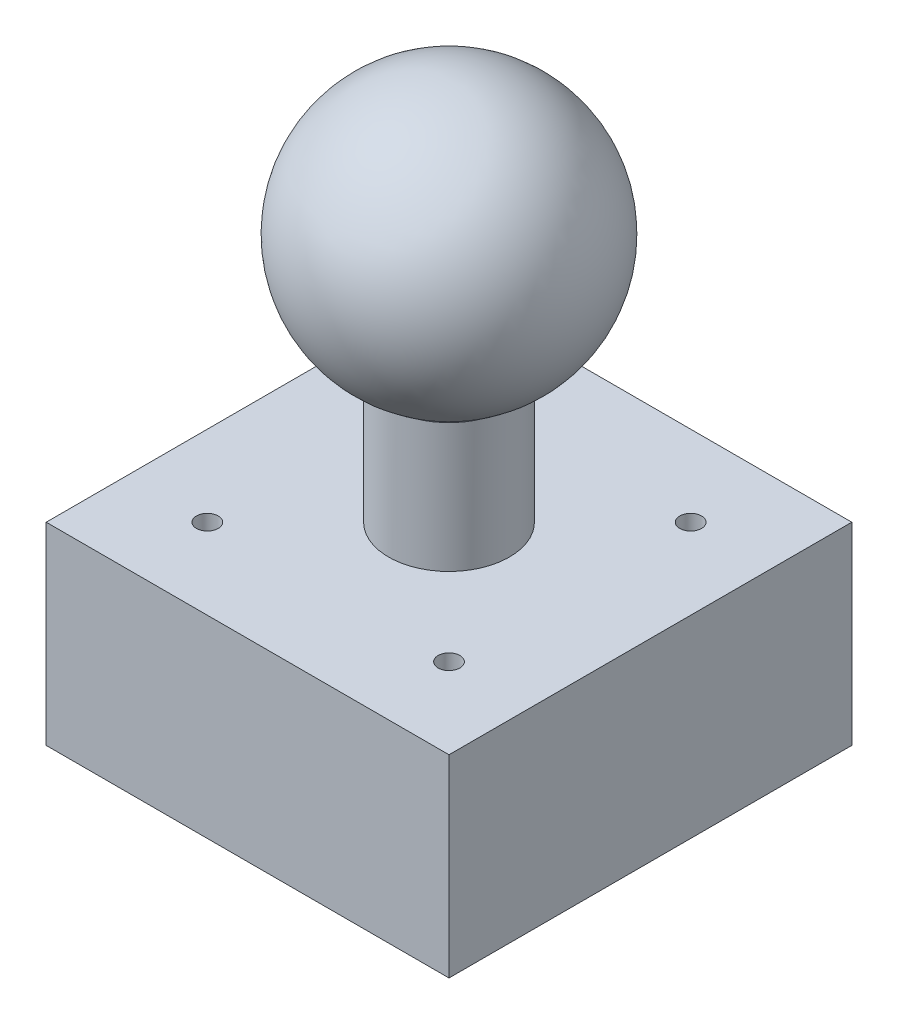
SolidWorks part; units mm, degrees
ref_plane "Alzado" through (0, 0, 0) normal (0, 0, 1) x (1, 0, 0)
ref_plane "Planta" through (0, 0, 0) normal (0, 1, 0) x (1, 0, 0)
ref_plane "Vista lateral" through (0, 0, 0) normal (1, 0, 0) x (0, 0, -1)
sketch "Croquis1" plane through (0, 0, 0) normal (0, 1, 0) x (1, 0, 0)
  line L0 (0, 13.8067) -> (0, 0) construction
  line L1 (-25, -25) -> (25, -25)
  line L2 (-25, -25) -> (-25, 25)
  line L3 (-25, 25) -> (25, 25)
  line L4 (25, -25) -> (25, 25)
  line L5 (-25, -25) -> (25, 25) construction
  line L6 (-25, 25) -> (25, -25) construction
  line L7 (0, 0) -> (7.6582, 0) construction
  circle A0 centre (-15, 15) radius 1.35
  circle A1 centre (15, 15) radius 1.35
  circle A2 centre (-15, -15) radius 1.35
  circle A3 centre (15, -15) radius 1.35
  point P0 (0, 0)
  dimension "D3" = 2.7
  dimension "D4" = 10
  dimension "D1" = 50
  dimension "D2" = 50
  dimension "D5" = 10
extrude "Saliente-Extruir1" add sketch "Croquis1" along normal blind 24
sketch "Croquis2" plane through (0, 0, 0) normal (0, 1, 0) x (1, 0, 0)
  circle A0 centre (0, 0) radius 7.5
  dimension "D1" = 15
extrude "Saliente-Extruir2" add sketch "Croquis2" along normal blind 40
ref_plane "Plano1" through (0, 55, 0) normal (0, 1, 0) x (1, 0, 0)
sketch "Croquis3" plane through (0, 55, 0) normal (0, 1, 0) x (1, 0, 0)
  line L0 (0, 16.5) -> (0, -16.5)
  arc A0 (0, -16.5) -> (0, 16.5) centre (0, 0) ccw
  dimension "D1" = 33
revolve "Revolución1" add sketch "Croquis3" angle 360 about L0
sketch "55 MM" plane through (0, 0, 0) normal (0, 0, 1) x (1, 0, 0)
  line L0 (0, 55) -> (0, 0) construction
  line L1 (27.5, 55) -> (-27.5, 55) construction
  dimension "D1" = 55
